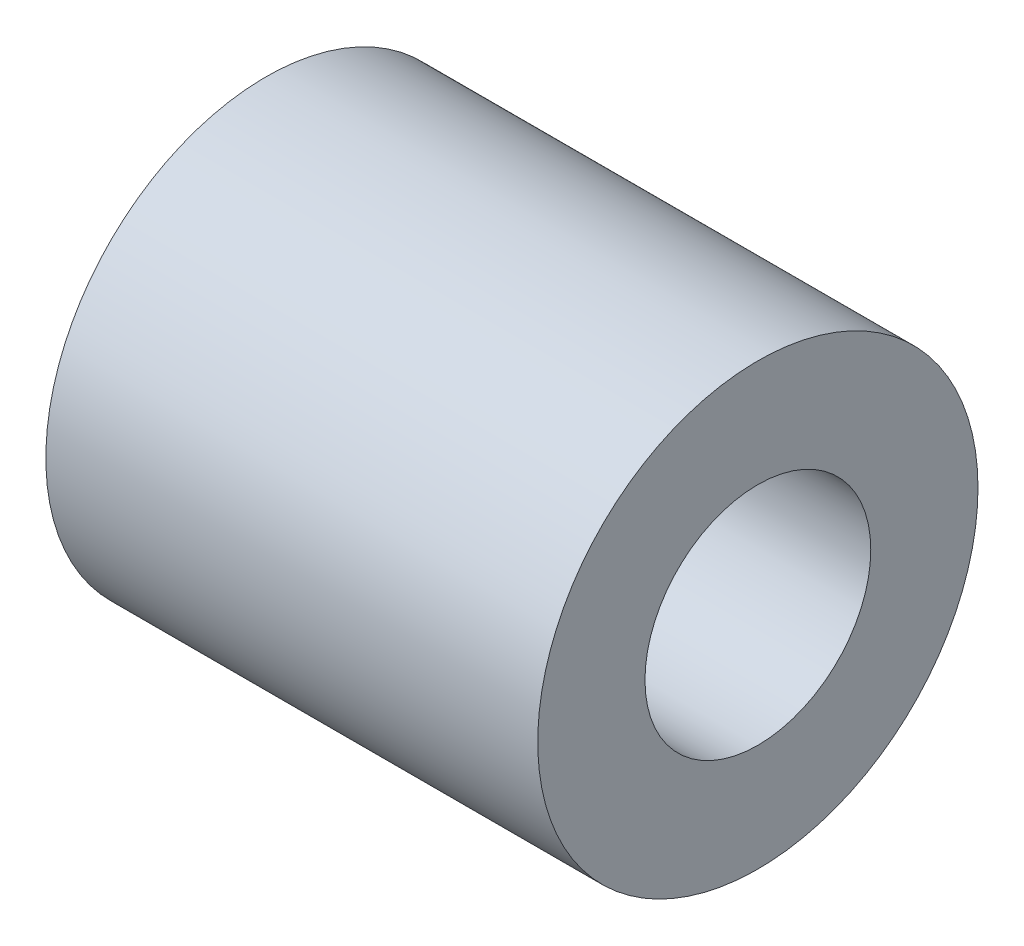
SolidWorks part; units mm, degrees
ref_plane "Piano frontale" through (0, 0, 0) normal (0, 0, 1) x (1, 0, 0)
ref_plane "Piano superiore" through (0, 0, 0) normal (0, 1, 0) x (1, 0, 0)
ref_plane "Piano destro" through (0, 0, 0) normal (1, 0, 0) x (0, 0, -1)
sketch "Schizzo2" plane through (0, 0, 0) normal (1, 0, 0) x (0, 0, -1)
  circle A0 centre (0, 0) radius 3.88
  circle A1 centre (0, 0) radius 1.99
  dimension "D1" = 7.76
  dimension "D2" = 3.98
extrude "Estrusione-Estrusione1" add sketch "Schizzo2" along normal mid plane 8.67
